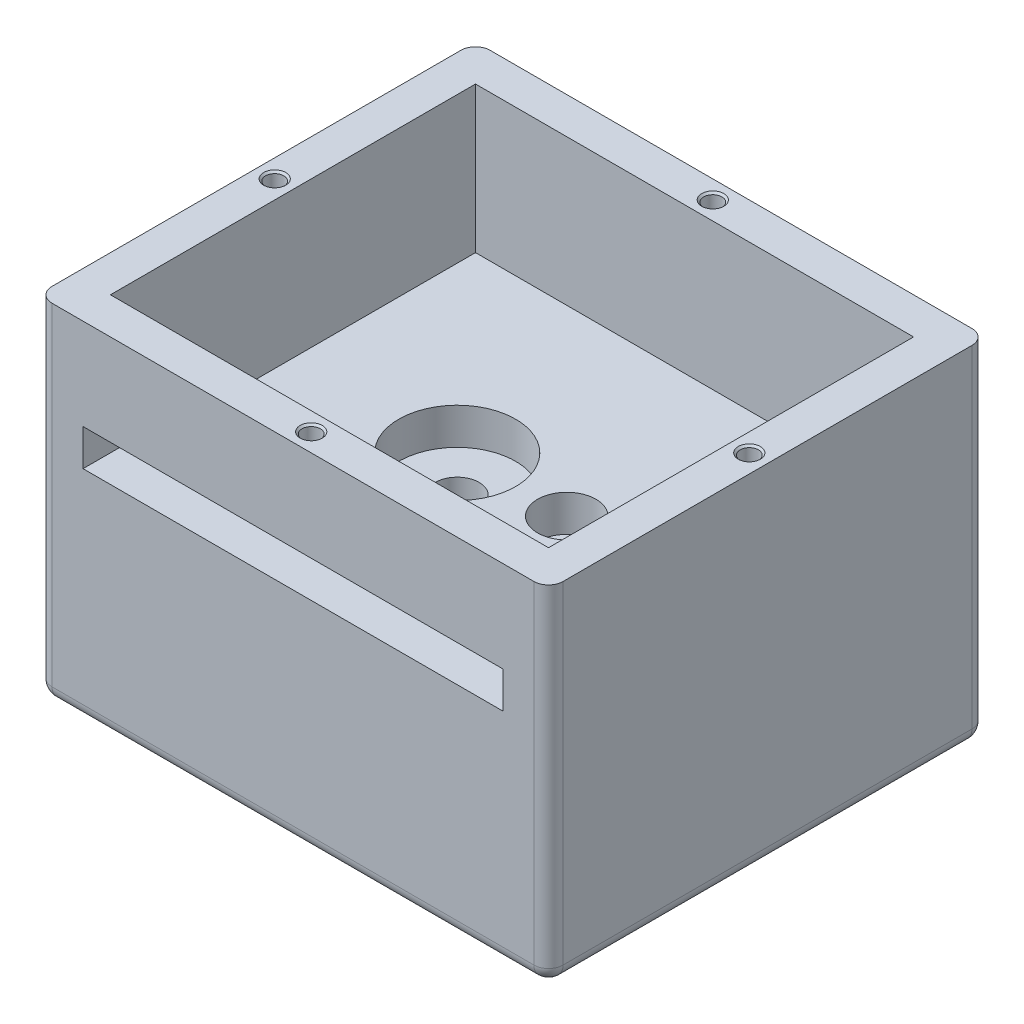
SolidWorks part; units mm, degrees
ref_plane "前视基准面" through (0, 0, 0) normal (0, 0, 1) x (1, 0, 0)
ref_plane "上视基准面" through (0, 0, 0) normal (0, 1, 0) x (1, 0, 0)
ref_plane "右视基准面" through (0, 0, 0) normal (1, 0, 0) x (0, 0, -1)
other "Configuration Table"
sketch "Box_top_view" plane through (0, 0, 0) normal (0, 1, 0) x (1, 0, 0)
  line L1 (-70, -60) -> (70, -60)
  line L2 (-70, -60) -> (-70, 60)
  line L3 (-70, 60) -> (70, 60)
  line L4 (70, -60) -> (70, 60)
  point P4 (-70, 0)
  point P6 (0, 60)
  dimension "D1" = 140
  dimension "D2" = 120
extrude "Box_extrude_part" add sketch "Box_top_view" along normal blind 80 and the other way blind 15
sketch "Scissor_crossSection" plane through (0, 0, 60) normal (0, 0, 1) x (1, 0, 0)
  line L0 (-70, -15) -> (70, -15) construction
  line L1 (-57.5, 55) -> (57.5, 55)
  line L2 (-57.5, 55) -> (-57.5, 45)
  line L3 (-57.5, 45) -> (57.5, 45)
  line L4 (57.5, 55) -> (57.5, 45)
  point P4 (0, 55)
  point P6 (57.5, 50)
  dimension "D1" = 10
  dimension "D2" = 115
  dimension "D3" = 65
sketch "Inner_box_cut" plane through (0, 80, 0) normal (0, 1, 0) x (1, 0, 0)
  line L1 (-60, 50) -> (60, 50)
  line L2 (-60, 50) -> (-60, -50)
  line L3 (-60, -50) -> (60, -50)
  line L4 (60, 50) -> (60, -50)
  point P5 (0, 50)
  point P7 (-60, 0)
  dimension "D1" = 120
  dimension "D2" = 100
extrude "Inner_box_cut_1" cut sketch "Inner_box_cut" against normal blind 40
extrude "Scissor_corssSection_cut" cut sketch "Scissor_crossSection" against normal blind 10
sketch "Shaft_location" plane through (0, 40, 0) normal (0, 1, 0) x (1, 0, 0)
  line L0 (0, 21.009) -> (0, -18.7201) construction
  circle A0 centre (15, 0) radius 6
  circle A1 centre (-15, 0) radius 6
  dimension "D1" = 12
  dimension "D2" = 15
extrude "Shaft_location_cut" cut sketch "Shaft_location" against normal blind 40 contours A0 | A1
sketch "Sketch2" plane through (0, 40, 0) normal (0, 1, 0) x (1, 0, 0)
  circle A1 centre (-15, 0) radius 16
  circle A2 centre (15, 0) radius 8
  dimension "D1" = 32
  dimension "D2" = 16
extrude "Bearing_location_cut1" cut sketch "Sketch2" against normal blind 10
sketch "Hole_location" plane through (0, 80, 0) normal (0, 1, 0) x (1, 0, 0)
  line L0 (0, 30.1647) -> (0, -21.1725) construction
  line L1 (-34.0069, 0) -> (33.6799, 0) construction
  point P5 (-65, 0)
  point P6 (0, 55)
  dimension "D1" = 65
  dimension "D2" = 55
hole_wizard "M6 Tapped Hole3" positions "3DSketch3" profile "Sketch7" tap size "M6" standard "ISO"
sketch3d "3DSketch3"
  point P0 (0, 80, -55)
  point P3 (-65, 80, 0)
cosmetic thread "Hole Thread7" parameters "D1"=10, "D2"=6
cosmetic thread "Hole Thread8" parameters "D1"=10, "D2"=6
sketch "Sketch7" plane through (0, 80, -55) normal (1, 0, 0) x (0, 0, 1)
  line L0 (0, 0) -> (0, 14.5022)
  line L1 (0, 14.5022) -> (2.5, 13)
  line L2 (2.5, 13) -> (2.5, 0.525)
  line L3 (2.5, 0.525) -> (3.025, 0)
  line L5 (3.025, 0) -> (0, 0)
  line L6 (-2.5, 0.525) -> (-3.025, 0) construction
  line L10 (0, 14.5022) -> (-2.5, 13) construction
  line L11 (0, -6.35) -> (0, 107.95) construction
  dimension "Tap Drill Dia." = 5
  dimension "Tap Drill Depth" = 13
  dimension "Near C'Sink Dia." = 6.05
  dimension "Near C'Sink Angle" = 90
  dimension "Drill Angle" = 118
mirror "M6_hole_mirror" about plane through (0, 0, 0) normal (1, 0, 0) of "M6 Tapped Hole3" second plane through (0, 0, 0) second plane normal (0, 0, 1)
fillet "Edges_fillet" radius 4 8 edges at (-70, -15, 0) (0, -15, -60) (0, -15, 60) (70, -15, 0) (-70, 32.5, -60) (70, 32.5, -60) (70, 32.5, 60) (-70, 32.5, 60)
